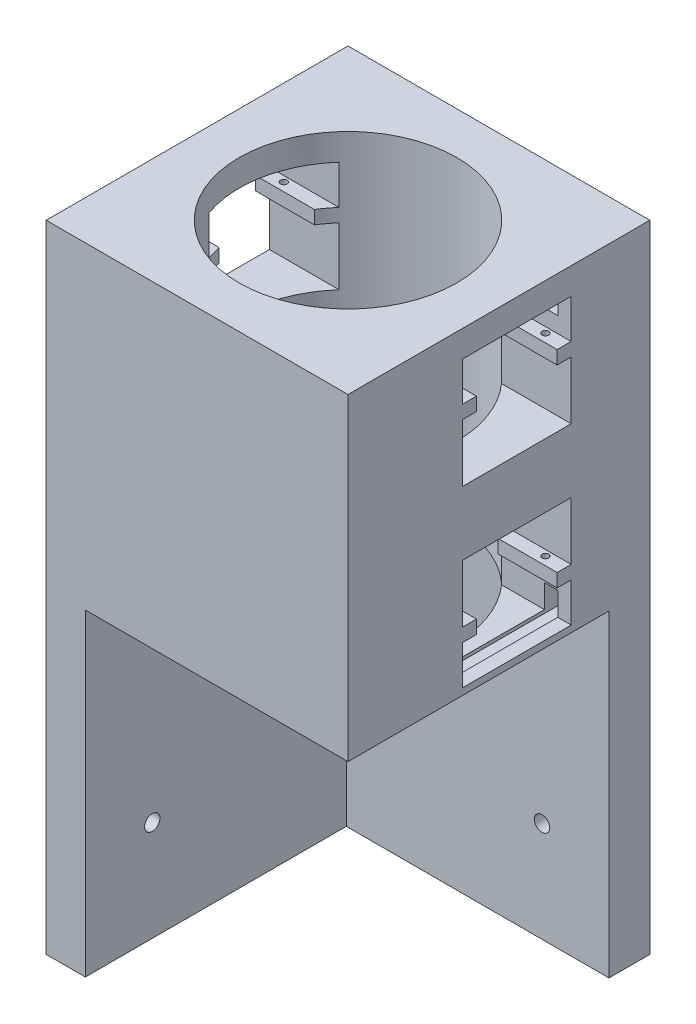
SolidWorks part; units mm, degrees
ref_plane "Front Plane" through (0, 0, 0) normal (0, 0, 1) x (1, 0, 0)
ref_plane "Top Plane" through (0, 0, 0) normal (0, 1, 0) x (1, 0, 0)
ref_plane "Right Plane" through (0, 0, 0) normal (1, 0, 0) x (0, 0, -1)
sketch "Sketch2" plane through (0, 0, 0) normal (0, 1, 0) x (1, 0, 0)
  line L0 (45.1, 45.1) -> (45.1, -45.1)
  line L1 (-32.5, 32.5) -> (32.5, 32.5) construction
  line L2 (-32.5, 32.5) -> (-32.5, -32.5) construction
  line L3 (-32.5, -32.5) -> (32.5, -32.5) construction
  line L4 (32.5, 32.5) -> (32.5, -32.5) construction
  line L5 (-32.5, 32.5) -> (32.5, -32.5) construction
  line L6 (-32.5, -32.5) -> (32.5, 32.5) construction
  line L7 (-45.1, -45.1) -> (45.1, -45.1)
  line L8 (-45.1, 45.1) -> (-45.1, -45.1)
  line L9 (-45.1, 45.1) -> (45.1, 45.1)
  circle A0 centre (0, 0) radius 32.5
  dimension "D1" = 65
  dimension "D2" = 12.6
extrude "Boss-Extrude2" add sketch "Sketch2" along normal blind 250
sketch "Sketch3" plane through (0, 0, 45.1) normal (0, 0, 1) x (1, 0, 0)
  line L1 (45.1, 0) -> (-33.4, 0)
  line L2 (45.1, 0) -> (45.1, 115)
  line L3 (45.1, 115) -> (-33.4, 115)
  line L4 (-33.4, 0) -> (-33.4, 115)
  dimension "D1" = 78.5
  dimension "D2" = 115
extrude "Cut-Extrude1" cut sketch "Sketch3" against normal blind 78
sketch "Sketch6" plane through (45.1, 0, 0) normal (1, 0, 0) x (0, 0, -1)
  line L10 (-10.9, 150) -> (-10.9, 117)
  line L11 (-10.9, 117) -> (21.6, 117)
  line L13 (-10.9, 150) -> (21.6, 150)
  line L14 (21.6, 117) -> (21.6, 150)
  dimension "D1" = 33
  dimension "D3" = 32.5
extrude "Cut-Extrude4" cut sketch "Sketch6" against normal blind 32.6
sketch "Sketch7" plane through (45.1, 0, 0) normal (1, 0, 0) x (0, 0, -1)
  line L0 (-10.9, 117) -> (-10.9, 132.7)
  line L1 (-10.9, 150) -> (-10.9, 117) construction
  dimension "D1" = 15.7
mirror "Mirror1" about plane through (0, 0, 0) normal (1, 0, 0) of "Cut-Extrude4"
ref_plane "Plane1" through (0, 159.55, 0) normal (0, -1, 0) x (-1, 0, 0)
mirror "Mirror2" about plane through (0, 159.55, 0) normal (0, -1, 0) of "Cut-Extrude4"
mirror "Mirror3" about plane through (0, 0, 0) normal (1, 0, 0) of "Mirror2"
sketch "Sketch10" plane through (0, 0, -45.1) normal (0, 0, -1) x (-1, 0, 0)
  line L4 (-41.1, 203.1) -> (-41.1, 195.1)
  line L7 (-41.1, 203.1) -> (-37.1, 203.1)
  line L9 (-41.1, 195.1) -> (-37.1, 195.1)
  line L10 (-37.1, 203.1) -> (-37.1, 195.1)
  dimension "D1" = 8
  dimension "D2" = 4
extrude "Cut-Extrude5" cut sketch "Sketch10" against normal up to surface and the other way through all up to face at (37.8588, 185.6, 10.9)
sketch "Sketch11" plane through (0, 0, -45.1) normal (0, 0, -1) x (-1, 0, 0)
  line L1 (-41.1, 195.1) -> (-37.1, 195.1)
  line L2 (-41.1, 195.1) -> (-41.1, -4.9)
  line L3 (-41.1, -4.9) -> (-37.1, -4.9)
  line L4 (-37.1, 195.1) -> (-37.1, -4.9)
  dimension "D1" = 200
extrude "Cut-Extrude6" cut sketch "Sketch11" against normal blind 3
mirror "Mirror4" about plane through (0, 159.55, 0) normal (0, -1, 0) of "Cut-Extrude5"
mirror "Mirror5" about plane through (0, 0, 0) normal (1, 0, 0) of "Cut-Extrude5"
mirror "Mirror6" about plane through (0, 0, 0) normal (1, 0, 0) of "Cut-Extrude6"
mirror "Mirror7" about plane through (0, 0, 0) normal (1, 0, 0) of "Mirror4"
ref_plane "Plane2" through (0, 0, -5.35) normal (0, 0, -1) x (-1, 0, 0)
sketch "Sketch12" plane through (0, 0, -21.6) normal (0, 0, 1) x (1, 0, 0)
  line L0 (45.1, 186.4) -> (45.1, 190.4)
  line L1 (45.1, 202.1) -> (45.1, 169.1) construction
  line L2 (24.2835, 169.1) -> (24.2835, 202.1) construction
  line L3 (45.1, 186.4) -> (24.2835, 186.4)
  line L5 (45.1, 190.4) -> (24.2835, 190.4)
  line L6 (24.2835, 186.4) -> (24.2835, 190.4)
  dimension "D2" = 4
extrude "Boss-Extrude3" add sketch "Sketch12" along normal blind 4.2
sketch "Sketch13" plane through (0, 190.4, 0) normal (0, 1, 0) x (1, 0, 0)
  line L0 (45.1, 21.6) -> (45.1, 19.91) construction
  line L1 (45.1, 17.4) -> (45.1, 21.6) construction
  line L3 (45.1, 19.91) -> (39.1, 19.91) construction
  circle A0 centre (39.1, 19.91) radius 1
  dimension "D3" = 2
  dimension "D1" = 1.69
  dimension "D2" = 6
extrude "Cut-Extrude7" cut sketch "Sketch13" against normal blind 10
mirror "Mirror8" about plane through (0, 0, -5.35) normal (0, 0, -1) of "Cut-Extrude7", "Boss-Extrude3"
mirror "Mirror9" about plane through (0, 159.55, 0) normal (0, -1, 0) of "Mirror8", "Cut-Extrude7", "Boss-Extrude3"
mirror "Mirror10" about plane through (0, 0, 0) normal (1, 0, 0) of "Cut-Extrude7", "Mirror8", "Mirror9", "Boss-Extrude3"
sketch "Sketch14" plane through (0, 250, 0) normal (0, 1, 0) x (1, 0, 0)
  circle A0 centre (0, 0) radius 32.5
extrude "Cut-Extrude8" cut sketch "Sketch14" against normal blind 1000
sketch "Sketch15" plane through (45.1, 0, 0) normal (1, 0, 0) x (0, 0, -1)
  line L0 (-45.1, 250) -> (-45.1, 115) construction
  line L1 (45.1, 250) -> (-45.1, 250)
  line L2 (45.1, 250) -> (45.1, 210.0258)
  line L3 (45.1, 210.0258) -> (-45.1, 210.0258)
  line L4 (-45.1, 250) -> (-45.1, 210.0258)
extrude "Cut-Extrude9" cut sketch "Sketch15" against normal through all
sketch "Sketch16" plane through (45.1, 0, 0) normal (1, 0, 0) x (0, 0, -1)
  line L0 (-45.1, 115) -> (-45.1, 0) construction
  line L1 (45.1, 0) -> (-45.1, 0)
  line L2 (45.1, 0) -> (45.1, 20)
  line L3 (45.1, 20) -> (-45.1, 20)
  line L4 (-45.1, 0) -> (-45.1, 20)
  dimension "D1" = 20
extrude "Cut-Extrude10" cut sketch "Sketch16" against normal through all
ref_plane "Plane3" through (0, 133.5, 0) normal (0, -1, 0) x (-1, 0, 0)
ref_plane "Plane4" through (0, 185.6, 0) normal (0, -1, 0) x (-1, 0, 0)
sketch "Sketch19" plane through (-45.1, 0, 0) normal (-1, 0, 0) x (0, 0, 1)
  line L0 (0, -49.61) -> (0, 49.61) construction
  circle A0 centre (-25.1, 50) radius 2.3
  circle A1 centre (25.1, 50) radius 2.3
  dimension "D1" = 4.6
extrude "Cut-Extrude11" cut sketch "Sketch19" against normal through all
pattern_circular "CirPattern1" count 2 every 90 about axis through (0, 210.0258, 0) along (0, -1, 0) of "Cut-Extrude11"
